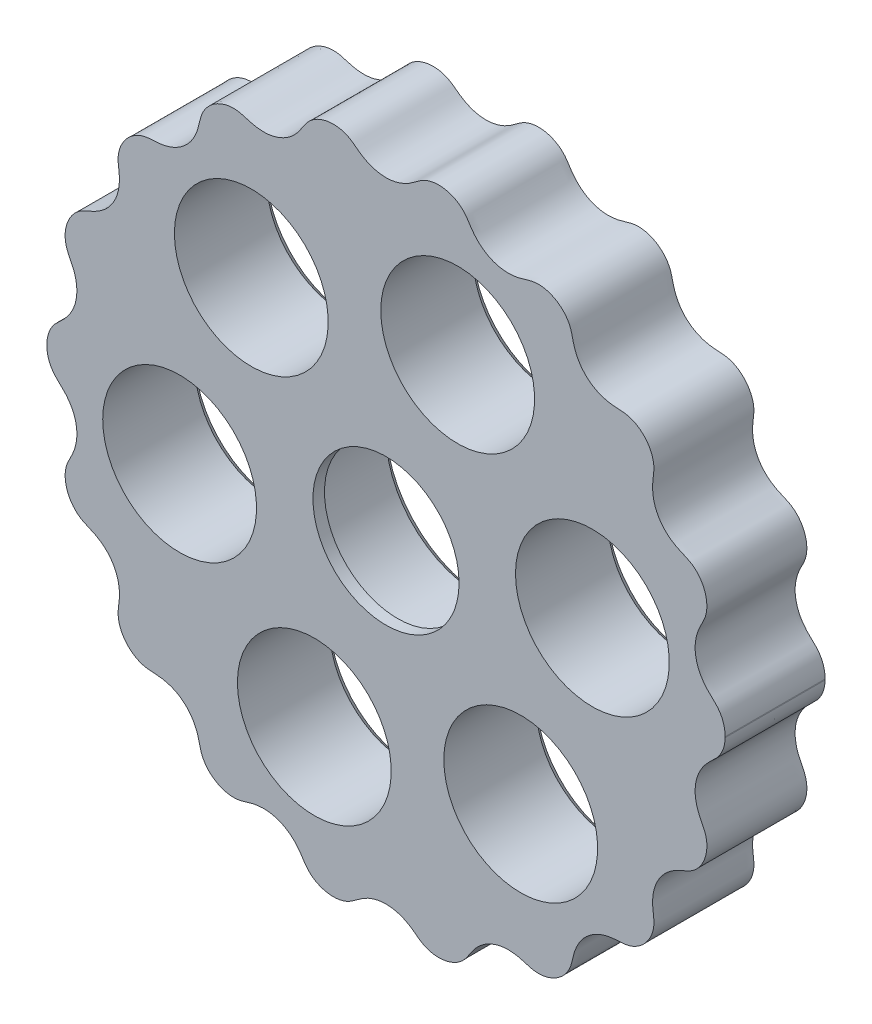
SolidWorks part; units mm, degrees
ref_plane "Front Plane" through (0, 0, 0) normal (0, 0, 1) x (1, 0, 0)
ref_plane "Top Plane" through (0, 0, 0) normal (0, 1, 0) x (1, 0, 0)
ref_plane "Right Plane" through (0, 0, 0) normal (1, 0, 0) x (0, 0, -1)
sketch "Sketch1" plane through (0, 0, 0) normal (0, 0, 1) x (1, 0, 0)
  line L0 (0, 0) -> (71.5354, 0) construction
  line L1 (0, 0) -> (26.836, 4.7319) construction
  arc A0 (44.0985, -0.1203) -> (44.1, 0) centre (39.3924, 0) ccw
  circle A1 centre (0, 0) radius 12
  circle A2 centre (26.836, 4.7319) radius 10
  circle A3 centre (17.516, -20.8747) radius 10
  circle A4 centre (-9.32, -25.6066) radius 10
  circle A5 centre (-26.836, -4.7319) radius 10
  circle A6 centre (-17.516, 20.8747) radius 10
  circle A7 centre (9.32, 25.6066) radius 10
  spline S0 degree 4 poles (36.6767, -18.9558) (36.8635, -18.7987) (37.1568, -18.579) (37.5707, -18.3184) (38.1155, -18.0434) (38.5626, -17.8474) (39.0142, -17.663) (39.4567, -17.456) (39.9012, -17.1807) (40.3307, -16.827) (40.8354, -16.2774) (41.3043, -15.523) (41.6465, -14.5868) (41.7649, -13.5582) (41.6813, -12.7422) (41.4951, -12.1162) (41.2986, -11.6694) (41.1215, -11.3218) (40.8977, -10.8888) (40.649, -10.3583) (40.4142, -9.7146) (40.1974, -8.7592) (40.1486, -7.6129) (40.3906, -6.3196) (40.9635, -5.1322) (41.587, -4.3265) (42.1201, -3.7892) (42.487, -3.4498) (42.7801, -3.1781) (43.1277, -2.8182) (43.4078, -2.4428) (43.6222, -2.0645) (43.7821, -1.6974) (43.8734, -1.446) (43.9495, -1.19) (44.0102, -0.9293) (44.0501, -0.6984) (44.0747, -0.5033) (44.0889, -0.3315) (44.0965, -0.1882) (44.1004, -0.0512) (44.1003, 0.0575) (44.0961, 0.2002) (44.0877, 0.3516) (44.0718, 0.5312) (44.0443, 0.7371) (44.0062, 0.9465) (43.9574, 1.1527) (43.9002, 1.3564) (43.8124, 1.6248) (43.6759, 1.9561) (43.4704, 2.3388) (43.1973, 2.7268) (42.9028, 3.0591) (42.5811, 3.3642) (42.2543, 3.6633) (41.857, 4.0496) (41.4472, 4.5088) (41.0516, 5.0585) (40.6188, 5.8583) (40.2694, 6.862) (40.1379, 7.9369) (40.2404, 9.0241) (40.4824, 9.9238) (40.7241, 10.5303) (40.9711, 11.0329) (41.23, 11.5305) (41.4742, 12.0369) (41.6912, 12.7506) (41.7643, 13.6759) (41.6231, 14.6695) (41.2345, 15.6741) (40.6786, 16.4957) (40.0904, 17.0544) (39.5529, 17.4028) (39.1287, 17.6105) (38.7812, 17.7582) (38.3459, 17.9401) (37.6896, 18.2421) (36.8537, 18.748) (35.9651, 19.5642) (35.2253, 20.6754) (34.8042, 21.8218) (34.6582, 22.7995) (34.6551, 23.5837) (34.7014, 24.1649) (34.7588, 24.6276) (34.819, 25.0899) (34.8465, 25.5562) (34.8182, 26.0519) (34.7221, 26.5691) (34.5055, 27.2363) (34.094, 28.0103) (33.4389, 28.7967) (32.6453, 29.3765) (31.9237, 29.701) (31.3397, 29.8541) (30.9247, 29.9174) (30.5063, 29.9454) (30.0877, 29.9633) (29.5648, 29.9977) (28.7961, 30.0962) (27.8011, 30.3642) (26.6402, 30.9641) (25.5501, 31.9548) (24.8466, 33.0536) (24.4844, 34.0219) (24.3027, 34.7493) (24.1799, 35.3002) (24.0444, 35.8492) (23.7558, 36.5419) (23.2182, 37.3055) (22.4721, 37.981) (21.5304, 38.5043) (20.5803, 38.7796) (19.7758, 38.834) (19.1432, 38.7607) (18.6866, 38.6509) (18.3273, 38.5424) (17.8796, 38.4022) (17.1879, 38.2098) (16.2295, 38.0541) (15.1511, 38.0927) (14.1001, 38.3568) (13.249, 38.7395) (12.5843, 39.159) (11.9777, 39.6706) (11.5076, 40.1878) (11.1477, 40.6723) (10.8676, 41.0971) (10.6491, 41.4405) (10.4195, 41.7769) (10.1616, 42.0928) (9.8452, 42.4081) (9.4641, 42.7096) (8.8955, 43.0565) (8.1021, 43.3731) (7.1136, 43.5515) (6.147, 43.4906) (5.3888, 43.281) (4.8443, 43.0283) (4.4861, 42.8141) (4.1483, 42.5698) (3.8181, 42.3158) (3.399, 42.0065) (2.753, 41.5865) (1.827, 41.1474) (0.5868, 40.8561) (-0.8258, 40.8878) (-2.0369, 41.2268) (-2.9229, 41.6848) (-3.5391, 42.1066) (-3.9385, 42.4083) (-4.2568, 42.6512) (-4.5868, 42.8786) (-4.9366, 43.0749) (-5.4733, 43.3086) (-6.2224, 43.5002) (-7.1565, 43.5453) (-8.2308, 43.3442) (-9.1419, 42.9461) (-9.7919, 42.4774) (-10.2304, 42.0207) (-10.5107, 41.6472) (-10.716, 41.3356) (-10.9671, 40.9426) (-11.3683, 40.3523) (-11.9933, 39.6173) (-12.9784, 38.8345) (-14.3072, 38.2427) (-15.622, 38.0386) (-16.7078, 38.119) (-17.5001, 38.2943) (-18.0183, 38.4446) (-18.4296, 38.575) (-18.8445, 38.6948) (-19.2689, 38.7773) (-19.7296, 38.8158) (-20.2217, 38.799) (-20.8742, 38.6969) (-21.6651, 38.435) (-22.5148, 37.9532) (-23.2004, 37.3139) (-23.6407, 36.7001) (-23.8979, 36.1889) (-24.0388, 35.8228) (-24.1457, 35.4456) (-24.2324, 35.0637) (-24.341, 34.5862) (-24.5432, 33.8399) (-24.9478, 32.8575) (-25.7396, 31.7268) (-26.8198, 30.8543) (-27.9055, 30.3412) (-28.8681, 30.0882) (-29.542, 29.9965) (-30.1085, 29.9625) (-30.655, 29.9382) (-31.2013, 29.8918) (-31.908, 29.7209) (-32.7236, 29.3297) (-33.437, 28.7738) (-34.0217, 28.0893) (-34.4319, 27.3875) (-34.6947, 26.7092) (-34.8184, 26.0998) (-34.8448, 25.586) (-34.8229, 25.1791) (-34.7914, 24.879) (-34.753, 24.5799) (-34.7164, 24.2805) (-34.6791, 23.9054) (-34.6547, 23.4533) (-34.6644, 22.9248) (-34.752, 22.1746) (-34.9928, 21.2469) (-35.4949, 20.1956) (-36.285, 19.2336) (-37.1129, 18.5857) (-37.8164, 18.1869) (-38.3337, 17.9455) (-38.7546, 17.7691) (-39.1754, 17.5922) (-39.5824, 17.3838) (-39.9866, 17.1147) (-40.376, 16.7794) (-40.8341, 16.2703) (-41.287, 15.5514) (-41.6373, 14.6281) (-41.7684, 13.5957) (-41.6841, 12.7484) (-41.4922, 12.1084) (-41.2953, 11.6627) (-41.1183, 11.3156) (-40.8949, 10.8831) (-40.6493, 10.3583) (-40.4186, 9.7263) (-40.2044, 8.7952) (-40.1455, 7.6523) (-40.3811, 6.3316) (-40.9655, 5.1189) (-41.6171, 4.2907) (-42.1615, 3.7501) (-42.5188, 3.4208) (-42.8029, 3.1556) (-43.1388, 2.8039) (-43.5356, 2.2681) (-43.902, 1.5016) (-44.1301, 0.4873) (-44.1153, -0.4997) (-43.9342, -1.3305) (-43.676, -1.9663) (-43.4233, -2.4149) (-43.1338, -2.8061) (-42.8211, -3.1409) (-42.4852, -3.4513) (-42.1496, -3.7619) (-41.7459, -4.1672) (-41.2216, -4.785) (-40.6667, -5.6805) (-40.2571, -6.8575) (-40.1492, -8.0179) (-40.2435, -8.9709) (-40.4198, -9.7036) (-40.5923, -10.2019) (-40.7703, -10.617) (-40.9338, -10.9558) (-41.0705, -11.2238) (-41.2084, -11.4912) (-41.3399, -11.762) (-41.4983, -12.1364) (-41.6474, -12.6276) (-41.7379, -13.2414) (-41.7216, -13.967) (-41.5738, -14.7731) (-41.2501, -15.6297) (-40.7493, -16.4152) (-40.1472, -17.0103) (-39.5948, -17.3794) (-39.1613, -17.5962) (-38.805, -17.7483) (-38.3581, -17.9346) (-37.6632, -18.2533) (-36.7684, -18.8026) (-35.9394, -19.6017) (-35.3162, -20.559) (-34.9501, -21.4361) (-34.754, -22.1735) (-34.6561, -22.9355) (-34.6539, -23.6107) (-34.7037, -24.19) (-34.7654, -24.6746) (-34.814, -25.0624) (-34.8415, -25.4527) (-34.8332, -25.844) (-34.765, -26.411) (-34.56, -27.1363) (-34.1301, -27.9767) (-33.4866, -28.7263) (-32.8171, -29.248) (-32.2156, -29.5706) (-31.7373, -29.7537) (-31.2675, -29.87) (-30.8155, -29.9284) (-30.361, -29.9515) (-29.9067, -29.9728) (-29.3398, -30.0211) (-28.5445, -30.1517) (-27.5467, -30.4714) (-26.4782, -31.095) (-25.6473, -31.8986) (-25.1024, -32.6745) (-24.7614, -33.3361) (-24.5688, -33.82) (-24.4344, -34.2453) (-24.3393, -34.6045) (-24.2708, -34.8937) (-24.2056, -35.1836) (-24.1369, -35.4728) (-24.0508, -35.7776) (-23.9368, -36.0939) (-23.7481, -36.5019) (-23.4494, -36.98) (-23.0222, -37.4813) (-22.3719, -38.029) (-21.544, -38.4954) (-20.7168, -38.7507) (-19.9455, -38.8252) (-19.36, -38.7875) (-18.9635, -38.7214) (-18.575, -38.6194) (-18.1922, -38.4994) (-17.7124, -38.3527) (-16.9871, -38.1681) (-15.9954, -38.0433) (-14.7404, -38.1435) (-13.4038, -38.602) (-12.3415, -39.3031) (-11.6253, -40.033) (-11.1642, -40.6483) (-10.8775, -41.0818) (-10.6541, -41.4324) (-10.3623, -41.8626) (-9.899, -42.3938) (-9.1869, -42.9321) (-8.2037, -43.3602) (-7.0734, -43.5529) (-6.1148, -43.4841) (-5.3713, -43.274) (-4.8379, -43.0245) (-4.4874, -42.8146) (-4.1564, -42.5758) (-3.8331, -42.3273) (-3.4233, -42.0238) (-2.7537, -41.584) (-1.7612, -41.114) (-0.4425, -40.8308) (1.0403, -40.9203) (2.2524, -41.3176) (3.0965, -41.7927) (3.6787, -42.2102) (4.0505, -42.4945) (4.3506, -42.7186) (4.7419, -42.9762) (5.3109, -43.2592) (6.0842, -43.4809) (7.0779, -43.5461) (8.1565, -43.3701) (9.0185, -43.0112) (9.656, -42.5787) (10.0808, -42.1789) (10.3429, -41.8772) (10.5757, -41.5527) (10.7913, -41.217) (11.062, -40.7981) (11.4933, -40.1917) (12.1633, -39.458) (13.1794, -38.7205) (14.4926, -38.1994) (15.7586, -38.0413) (16.7829, -38.1326) (17.5369, -38.3043) (18.0387, -38.4511) (18.4373, -38.5773) (18.8393, -38.693) (19.2503, -38.7741) (19.7068, -38.8152) (20.2045, -38.8013) (20.8784, -38.6982) (21.7056, -38.4205) (22.4637, -37.9777) (23.1147, -37.3897) (23.5463, -36.8348) (23.8129, -36.3801) (24.0082, -35.9224) (24.1409, -35.4736) (24.2423, -35.0176) (24.3472, -34.5622) (24.5038, -33.9993) (24.7774, -33.2626) (25.2526, -32.3934) (26.0445, -31.4622) (27.1225, -30.6755) (28.2369, -30.2168) (29.1936, -30.0303) (29.912, -29.9724) (30.3823, -29.9506) (30.7585, -29.9304) (31.2269, -29.8792) (31.8494, -29.734) (32.5908, -29.4093) (33.3924, -28.8267) (34.1, -28.0146) (34.5716, -27.1275) (34.818, -26.2303) (34.8559, -25.4836) (34.798, -24.9232) (34.725, -24.3656) (34.6454, -23.6229) (34.6499, -22.5928) (34.9244, -21.3341) (35.5841, -20.0498) (36.4432, -19.0874) (37.2687, -18.4847) (37.9615, -18.1146) (38.4661, -17.8887) (38.8747, -17.7199) (39.2802, -17.5429) (39.6692, -17.3307) (40.0569, -17.059) (40.4321, -16.7224) (40.8754, -16.2125) (41.3225, -15.4793) (41.6159, -14.6641) (41.7389, -13.805) (41.7166, -13.1062) (41.6324, -12.5888) (41.4921, -12.1142) (41.3092, -11.6862) (41.0959, -11.2734) (40.8838, -10.86) (40.6409, -10.3322) (40.3736, -9.5978) (40.1722, -8.6335) (40.1685, -7.4139) (40.4758, -6.1143) (41.0266, -5.0381) (41.638, -4.2711) (42.152, -3.7595) (42.4998, -3.4381) (42.7773, -3.1801) (43.1073, -2.8399) (43.4176, -2.4332) (43.6529, -2.012) (43.8242, -1.5939) (43.9238, -1.2824) (43.9889, -1.0282) (44.033, -0.8034) (44.0616, -0.6126) (44.0796, -0.4441) (44.0904, -0.304) (44.0975, -0.1709) (44.1002, -0.0646) (44.0998, 0.0735) (44.0955, 0.2206) (44.0851, 0.3964) (44.0643, 0.597) (44.0285, 0.8351) (43.9716, 1.1035) (43.8986, 1.3677) (43.8096, 1.6271) (43.6583, 1.9911) (43.4135, 2.4438) (43.0871, 2.8775) (42.6816, 3.2715) (42.2656, 3.653) (41.7268, 4.1708) (41.0686, 4.9615) (40.4759, 6.0882) (40.1559, 7.4652) (40.1801, 8.7282) (40.4033, 9.7014) (40.6813, 10.4269) (40.92, 10.9322) (41.1253, 11.3291) (41.3284, 11.7273) (41.5005, 12.1406) (41.6361, 12.607) (41.7187, 13.1243) (41.7383, 13.8359) (41.6034, 14.7228) (41.2341, 15.7008) (40.6514, 16.5314) (40.0399, 17.0906) (39.4907, 17.4365) (39.0646, 17.6413) (38.6279, 17.8207) (38.1942, 18.0075) (37.6639, 18.2672) (37.259, 18.512) (36.9707, 18.7184) (36.7863, 18.8659) knots 0 0 0 0 0 0.002836 0.004253 0.005671 0.007089 0.008507 0.009925 0.011343 0.013148 0.014954 0.018566 0.021594 0.024621 0.026888 0.028021 0.029155 0.030288 0.031421 0.033688 0.03596 0.038232 0.042776 0.046922 0.051068 0.053391 0.054552 0.055714 0.056876 0.058037 0.060361 0.061137 0.061913 0.062689 0.063466 0.064242 0.065018 0.065406 0.065795 0.066183 0.066571 0.066981 0.067391 0.067801 0.068211 0.069031 0.069851 0.070261 0.070671 0.071491 0.073132 0.074419 0.075707 0.076995 0.078282 0.07957 0.080858 0.083433 0.085425 0.087418 0.091402 0.095715 0.097871 0.100027 0.102202 0.103289 0.104376 0.106551 0.108726 0.111902 0.115078 0.118109 0.12114 0.123333 0.12443 0.125527 0.126624 0.127721 0.129914 0.133921 0.137927 0.141605 0.145284 0.147993 0.149348 0.150703 0.152057 0.153412 0.154767 0.156121 0.157815 0.159508 0.162895 0.166245 0.169595 0.170813 0.17203 0.173248 0.174466 0.175684 0.176902 0.179337 0.183463 0.187589 0.191926 0.196263 0.19845 0.199544 0.200638 0.202826 0.205013 0.208208 0.211403 0.214416 0.217428 0.219609 0.2207 0.22179 0.222881 0.223971 0.226152 0.230133 0.234114 0.236391 0.238667 0.240943 0.24322 0.245585 0.246768 0.247951 0.249134 0.250316 0.251499 0.252682 0.254316 0.255951 0.25922 0.262551 0.265882 0.267093 0.268303 0.269514 0.270725 0.271935 0.273146 0.275567 0.279672 0.283776 0.287796 0.291816 0.294143 0.295306 0.29647 0.297633 0.298797 0.29996 0.301124 0.304426 0.307727 0.310722 0.313717 0.315886 0.31697 0.318054 0.319138 0.320223 0.322391 0.326347 0.330303 0.334707 0.33911 0.341618 0.342872 0.344126 0.34538 0.346634 0.347888 0.349142 0.350743 0.352343 0.355544 0.35877 0.361996 0.363134 0.364272 0.36541 0.366548 0.367686 0.368824 0.3711 0.375531 0.379962 0.384669 0.387023 0.389377 0.391497 0.392557 0.393618 0.395738 0.397859 0.400955 0.404052 0.406156 0.40826 0.410365 0.412469 0.413345 0.414222 0.415098 0.415975 0.416851 0.417727 0.41948 0.421233 0.422985 0.426491 0.43057 0.434649 0.437302 0.438628 0.439954 0.44128 0.442607 0.443933 0.445259 0.446911 0.448564 0.451868 0.455076 0.458283 0.460547 0.461678 0.46281 0.463942 0.465074 0.467337 0.46954 0.471743 0.476148 0.480544 0.48494 0.487199 0.488328 0.489458 0.490587 0.491717 0.493975 0.497176 0.500376 0.503687 0.505343 0.506999 0.508328 0.509657 0.510985 0.512314 0.513643 0.514972 0.51763 0.521717 0.525805 0.529302 0.531051 0.5328 0.534548 0.535423 0.536297 0.537171 0.538046 0.53892 0.539794 0.541894 0.543993 0.546093 0.548193 0.551381 0.55457 0.556821 0.557947 0.559072 0.560198 0.561324 0.563575 0.567955 0.572335 0.574545 0.576756 0.578967 0.581177 0.583449 0.584584 0.58572 0.586856 0.587991 0.589127 0.590263 0.593481 0.5967 0.599994 0.601641 0.603287 0.604609 0.605931 0.607253 0.608575 0.609897 0.611219 0.613863 0.617928 0.621994 0.625448 0.627175 0.628902 0.630629 0.631492 0.632356 0.63322 0.634083 0.634947 0.63581 0.636899 0.637987 0.640164 0.64234 0.644517 0.647826 0.651135 0.652301 0.653467 0.654633 0.655799 0.656965 0.658131 0.660463 0.664492 0.668521 0.672617 0.676713 0.679129 0.680337 0.681545 0.682753 0.683961 0.686377 0.689701 0.693025 0.6963 0.699576 0.700761 0.701947 0.703132 0.704317 0.705502 0.706687 0.709058 0.71362 0.718182 0.722153 0.726125 0.728301 0.729389 0.730477 0.731565 0.732653 0.73483 0.737836 0.740842 0.744132 0.747422 0.748581 0.74974 0.7509 0.752059 0.753218 0.754378 0.756697 0.760702 0.764708 0.768825 0.772943 0.775373 0.776588 0.777804 0.779019 0.780234 0.781449 0.782664 0.784335 0.786007 0.789349 0.792743 0.79444 0.796137 0.797495 0.798852 0.80021 0.801567 0.802925 0.804282 0.806998 0.810684 0.81437 0.818367 0.822363 0.824552 0.825646 0.826741 0.827835 0.82893 0.831119 0.834143 0.837166 0.84035 0.843533 0.845713 0.847892 0.848982 0.850072 0.852251 0.856573 0.860895 0.864871 0.868848 0.871417 0.872702 0.873987 0.875272 0.876557 0.877842 0.879127 0.880763 0.8824 0.885674 0.889049 0.890737 0.892425 0.893775 0.895125 0.896475 0.897825 0.899175 0.900525 0.903225 0.906891 0.910557 0.914579 0.9186 0.920802 0.921903 0.923004 0.924105 0.925206 0.927407 0.928928 0.929689 0.930449 0.93121 0.93197 0.93235 0.93273 0.933111 0.933491 0.933889 0.934287 0.934686 0.935084 0.93588 0.936677 0.937473 0.938269 0.939066 0.939862 0.94205 0.944237 0.945331 0.946425 0.948612 0.952921 0.957229 0.96105 0.964871 0.967468 0.968766 0.970065 0.971364 0.972662 0.973961 0.97526 0.976997 0.978734 0.982209 0.985617 0.989025 0.990397 0.991769 0.99314 0.994512 0.995884 0.997256 1 1 1 1 1 construction
  spline S1 degree 4 poles (44.1, 0) (44.1, 0.0306) (44.0993, 0.0917) (44.0961, 0.2002) (44.0877, 0.3516) (44.0718, 0.5312) (44.0443, 0.7371) (44.0062, 0.9465) (43.9574, 1.1527) (43.9002, 1.3564) (43.8124, 1.6248) (43.6759, 1.9561) (43.4704, 2.3388) (43.1973, 2.7268) (42.9028, 3.0591) (42.5811, 3.3642) (42.2543, 3.6633) (41.857, 4.0496) (41.4472, 4.5088) (41.0516, 5.0585) (40.6188, 5.8583) (40.2694, 6.862) (40.1379, 7.9369) (40.2404, 9.0241) (40.4824, 9.9238) (40.7241, 10.5303) (40.9711, 11.0329) (41.23, 11.5305) (41.4742, 12.0369) (41.6912, 12.7506) (41.7643, 13.6759) (41.6231, 14.6695) (41.2345, 15.6741) (40.6786, 16.4957) (40.0904, 17.0544) (39.5529, 17.4028) (39.1287, 17.6105) (38.7812, 17.7582) (38.3459, 17.9401) (37.6896, 18.2421) (36.8537, 18.748) (35.9651, 19.5642) (35.2253, 20.6754) (34.8042, 21.8218) (34.6582, 22.7995) (34.6551, 23.5837) (34.7014, 24.1649) (34.7588, 24.6276) (34.819, 25.0899) (34.8465, 25.5562) (34.8182, 26.0519) (34.7221, 26.5691) (34.5055, 27.2363) (34.094, 28.0103) (33.4389, 28.7967) (32.6453, 29.3765) (31.9237, 29.701) (31.3397, 29.8541) (30.9247, 29.9174) (30.5063, 29.9454) (30.0877, 29.9633) (29.5648, 29.9977) (28.7961, 30.0962) (27.8011, 30.3642) (26.6402, 30.9641) (25.5501, 31.9548) (24.8466, 33.0536) (24.4844, 34.0219) (24.3027, 34.7493) (24.1799, 35.3002) (24.0444, 35.8492) (23.7558, 36.5419) (23.2182, 37.3055) (22.4721, 37.981) (21.5304, 38.5043) (20.5803, 38.7796) (19.7758, 38.834) (19.1432, 38.7607) (18.6866, 38.6509) (18.3273, 38.5424) (17.8796, 38.4022) (17.1879, 38.2098) (16.2295, 38.0541) (15.1511, 38.0927) (14.1001, 38.3568) (13.249, 38.7395) (12.5843, 39.159) (11.9777, 39.6706) (11.5076, 40.1878) (11.1477, 40.6723) (10.8676, 41.0971) (10.6491, 41.4405) (10.4195, 41.7769) (10.1616, 42.0928) (9.8452, 42.4081) (9.4641, 42.7096) (8.8955, 43.0565) (8.1021, 43.3731) (7.1136, 43.5515) (6.147, 43.4906) (5.3888, 43.281) (4.8443, 43.0283) (4.4861, 42.8141) (4.1483, 42.5698) (3.8181, 42.3158) (3.399, 42.0065) (2.753, 41.5865) (1.827, 41.1474) (0.5868, 40.8561) (-0.8258, 40.8878) (-2.0369, 41.2268) (-2.9229, 41.6848) (-3.5391, 42.1066) (-3.9385, 42.4083) (-4.2568, 42.6512) (-4.5868, 42.8786) (-4.9366, 43.0749) (-5.4733, 43.3086) (-6.2224, 43.5002) (-7.1565, 43.5453) (-8.2308, 43.3442) (-9.1419, 42.9461) (-9.7919, 42.4774) (-10.2304, 42.0207) (-10.5107, 41.6472) (-10.716, 41.3356) (-10.9671, 40.9426) (-11.3683, 40.3523) (-11.9933, 39.6173) (-12.9784, 38.8345) (-14.3072, 38.2427) (-15.622, 38.0386) (-16.7078, 38.119) (-17.5001, 38.2943) (-18.0183, 38.4446) (-18.4296, 38.575) (-18.8445, 38.6948) (-19.2689, 38.7773) (-19.7296, 38.8158) (-20.2217, 38.799) (-20.8742, 38.6969) (-21.6651, 38.435) (-22.5148, 37.9532) (-23.2004, 37.3139) (-23.6407, 36.7001) (-23.8979, 36.1889) (-24.0388, 35.8228) (-24.1457, 35.4456) (-24.2324, 35.0637) (-24.341, 34.5862) (-24.5432, 33.8399) (-24.9478, 32.8575) (-25.7396, 31.7268) (-26.8198, 30.8543) (-27.9055, 30.3412) (-28.8681, 30.0882) (-29.542, 29.9965) (-30.1085, 29.9625) (-30.655, 29.9382) (-31.2013, 29.8918) (-31.908, 29.7209) (-32.7236, 29.3297) (-33.437, 28.7738) (-34.0217, 28.0893) (-34.4319, 27.3875) (-34.6947, 26.7092) (-34.8184, 26.0998) (-34.8448, 25.586) (-34.8229, 25.1791) (-34.7914, 24.879) (-34.753, 24.5799) (-34.7164, 24.2805) (-34.6791, 23.9054) (-34.6547, 23.4533) (-34.6644, 22.9248) (-34.752, 22.1746) (-34.9928, 21.2469) (-35.4949, 20.1956) (-36.285, 19.2336) (-37.1129, 18.5857) (-37.8164, 18.1869) (-38.3337, 17.9455) (-38.7546, 17.7691) (-39.1754, 17.5922) (-39.5824, 17.3838) (-39.9866, 17.1147) (-40.376, 16.7794) (-40.8341, 16.2703) (-41.287, 15.5514) (-41.6373, 14.6281) (-41.7684, 13.5957) (-41.6841, 12.7484) (-41.4922, 12.1084) (-41.2953, 11.6627) (-41.1183, 11.3156) (-40.8949, 10.8831) (-40.6493, 10.3583) (-40.4186, 9.7263) (-40.2044, 8.7952) (-40.1455, 7.6523) (-40.3811, 6.3316) (-40.9655, 5.1189) (-41.6171, 4.2907) (-42.1615, 3.7501) (-42.5188, 3.4208) (-42.8029, 3.1556) (-43.1388, 2.8039) (-43.5356, 2.2681) (-43.902, 1.5016) (-44.1301, 0.4873) (-44.1153, -0.4997) (-43.9342, -1.3305) (-43.676, -1.9663) (-43.4233, -2.4149) (-43.1338, -2.8061) (-42.8211, -3.1409) (-42.4852, -3.4513) (-42.1496, -3.7619) (-41.7459, -4.1672) (-41.2216, -4.785) (-40.6667, -5.6805) (-40.2571, -6.8575) (-40.1492, -8.0179) (-40.2435, -8.9709) (-40.4198, -9.7036) (-40.5923, -10.2019) (-40.7703, -10.617) (-40.9338, -10.9558) (-41.0705, -11.2238) (-41.2084, -11.4912) (-41.3399, -11.762) (-41.4983, -12.1364) (-41.6474, -12.6276) (-41.7379, -13.2414) (-41.7216, -13.967) (-41.5738, -14.7731) (-41.2501, -15.6297) (-40.7493, -16.4152) (-40.1472, -17.0103) (-39.5948, -17.3794) (-39.1613, -17.5962) (-38.805, -17.7483) (-38.3581, -17.9346) (-37.6632, -18.2533) (-36.7684, -18.8026) (-35.9394, -19.6017) (-35.3162, -20.559) (-34.9501, -21.4361) (-34.754, -22.1735) (-34.6561, -22.9355) (-34.6539, -23.6107) (-34.7037, -24.19) (-34.7654, -24.6746) (-34.814, -25.0624) (-34.8415, -25.4527) (-34.8332, -25.844) (-34.765, -26.411) (-34.56, -27.1363) (-34.1301, -27.9767) (-33.4866, -28.7263) (-32.8171, -29.248) (-32.2156, -29.5706) (-31.7373, -29.7537) (-31.2675, -29.87) (-30.8155, -29.9284) (-30.361, -29.9515) (-29.9067, -29.9728) (-29.3398, -30.0211) (-28.5445, -30.1517) (-27.5467, -30.4714) (-26.4782, -31.095) (-25.6473, -31.8986) (-25.1024, -32.6745) (-24.7614, -33.3361) (-24.5688, -33.82) (-24.4344, -34.2453) (-24.3393, -34.6045) (-24.2708, -34.8937) (-24.2056, -35.1836) (-24.1369, -35.4728) (-24.0508, -35.7776) (-23.9368, -36.0939) (-23.7481, -36.5019) (-23.4494, -36.98) (-23.0222, -37.4813) (-22.3719, -38.029) (-21.544, -38.4954) (-20.7168, -38.7507) (-19.9455, -38.8252) (-19.36, -38.7875) (-18.9635, -38.7214) (-18.575, -38.6194) (-18.1922, -38.4994) (-17.7124, -38.3527) (-16.9871, -38.1681) (-15.9954, -38.0433) (-14.7404, -38.1435) (-13.4038, -38.602) (-12.3415, -39.3031) (-11.6253, -40.033) (-11.1642, -40.6483) (-10.8775, -41.0818) (-10.6541, -41.4324) (-10.3623, -41.8626) (-9.899, -42.3938) (-9.1869, -42.9321) (-8.2037, -43.3602) (-7.0734, -43.5529) (-6.1148, -43.4841) (-5.3713, -43.274) (-4.8379, -43.0245) (-4.4874, -42.8146) (-4.1564, -42.5758) (-3.8331, -42.3273) (-3.4233, -42.0238) (-2.7537, -41.584) (-1.7612, -41.114) (-0.4425, -40.8308) (1.0403, -40.9203) (2.2524, -41.3176) (3.0965, -41.7927) (3.6787, -42.2102) (4.0505, -42.4945) (4.3506, -42.7186) (4.7419, -42.9762) (5.3109, -43.2592) (6.0842, -43.4809) (7.0779, -43.5461) (8.1565, -43.3701) (9.0185, -43.0112) (9.656, -42.5787) (10.0808, -42.1789) (10.3429, -41.8772) (10.5757, -41.5527) (10.7913, -41.217) (11.062, -40.7981) (11.4933, -40.1917) (12.1633, -39.458) (13.1794, -38.7205) (14.4926, -38.1994) (15.7586, -38.0413) (16.7829, -38.1326) (17.5369, -38.3043) (18.0387, -38.4511) (18.4373, -38.5773) (18.8393, -38.693) (19.2503, -38.7741) (19.7068, -38.8152) (20.2045, -38.8013) (20.8784, -38.6982) (21.7056, -38.4205) (22.4637, -37.9777) (23.1147, -37.3897) (23.5463, -36.8348) (23.8129, -36.3801) (24.0082, -35.9224) (24.1409, -35.4736) (24.2423, -35.0176) (24.3472, -34.5622) (24.5038, -33.9993) (24.7774, -33.2626) (25.2526, -32.3934) (26.0445, -31.4622) (27.1225, -30.6755) (28.2369, -30.2168) (29.1936, -30.0303) (29.912, -29.9724) (30.3823, -29.9506) (30.7585, -29.9304) (31.2269, -29.8792) (31.8494, -29.734) (32.5908, -29.4093) (33.3924, -28.8267) (34.1, -28.0146) (34.5716, -27.1275) (34.818, -26.2303) (34.8559, -25.4836) (34.798, -24.9232) (34.725, -24.3656) (34.6454, -23.6229) (34.6499, -22.5928) (34.9244, -21.3341) (35.5841, -20.0498) (36.4432, -19.0874) (37.2687, -18.4847) (37.9615, -18.1146) (38.4661, -17.8887) (38.8747, -17.7199) (39.2802, -17.5429) (39.6692, -17.3307) (40.0569, -17.059) (40.4321, -16.7224) (40.8754, -16.2125) (41.3225, -15.4793) (41.6159, -14.6641) (41.7389, -13.805) (41.7166, -13.1062) (41.6324, -12.5888) (41.4921, -12.1142) (41.3092, -11.6862) (41.0959, -11.2734) (40.8838, -10.86) (40.6409, -10.3322) (40.3736, -9.5978) (40.1722, -8.6335) (40.1685, -7.4139) (40.4758, -6.1143) (41.0266, -5.0381) (41.638, -4.2711) (42.152, -3.7595) (42.4998, -3.4381) (42.7773, -3.1801) (43.1073, -2.8399) (43.4176, -2.4332) (43.6529, -2.012) (43.8242, -1.5939) (43.9238, -1.2824) (43.9889, -1.0282) (44.033, -0.8034) (44.0616, -0.6126) (44.0796, -0.4441) (44.0904, -0.304) (44.0957, -0.2053) (44.0977, -0.1486) (44.0985, -0.1203) knots 0.066571 0.066571 0.066571 0.066571 0.066571 0.066981 0.067391 0.067801 0.068211 0.069031 0.069851 0.070261 0.070671 0.071491 0.073132 0.074419 0.075707 0.076995 0.078282 0.07957 0.080858 0.083433 0.085425 0.087418 0.091402 0.095715 0.097871 0.100027 0.102202 0.103289 0.104376 0.106551 0.108726 0.111902 0.115078 0.118109 0.12114 0.123333 0.12443 0.125527 0.126624 0.127721 0.129914 0.133921 0.137927 0.141605 0.145284 0.147993 0.149348 0.150703 0.152057 0.153412 0.154767 0.156121 0.157815 0.159508 0.162895 0.166245 0.169595 0.170813 0.17203 0.173248 0.174466 0.175684 0.176902 0.179337 0.183463 0.187589 0.191926 0.196263 0.19845 0.199544 0.200638 0.202826 0.205013 0.208208 0.211403 0.214416 0.217428 0.219609 0.2207 0.22179 0.222881 0.223971 0.226152 0.230133 0.234114 0.236391 0.238667 0.240943 0.24322 0.245585 0.246768 0.247951 0.249134 0.250316 0.251499 0.252682 0.254316 0.255951 0.25922 0.262551 0.265882 0.267093 0.268303 0.269514 0.270725 0.271935 0.273146 0.275567 0.279672 0.283776 0.287796 0.291816 0.294143 0.295306 0.29647 0.297633 0.298797 0.29996 0.301124 0.304426 0.307727 0.310722 0.313717 0.315886 0.31697 0.318054 0.319138 0.320223 0.322391 0.326347 0.330303 0.334707 0.33911 0.341618 0.342872 0.344126 0.34538 0.346634 0.347888 0.349142 0.350743 0.352343 0.355544 0.35877 0.361996 0.363134 0.364272 0.36541 0.366548 0.367686 0.368824 0.3711 0.375531 0.379962 0.384669 0.387023 0.389377 0.391497 0.392557 0.393618 0.395738 0.397859 0.400955 0.404052 0.406156 0.40826 0.410365 0.412469 0.413345 0.414222 0.415098 0.415975 0.416851 0.417727 0.41948 0.421233 0.422985 0.426491 0.43057 0.434649 0.437302 0.438628 0.439954 0.44128 0.442607 0.443933 0.445259 0.446911 0.448564 0.451868 0.455076 0.458283 0.460547 0.461678 0.46281 0.463942 0.465074 0.467337 0.46954 0.471743 0.476148 0.480544 0.48494 0.487199 0.488328 0.489458 0.490587 0.491717 0.493975 0.497176 0.500376 0.503687 0.505343 0.506999 0.508328 0.509657 0.510985 0.512314 0.513643 0.514972 0.51763 0.521717 0.525805 0.529302 0.531051 0.5328 0.534548 0.535423 0.536297 0.537171 0.538046 0.53892 0.539794 0.541894 0.543993 0.546093 0.548193 0.551381 0.55457 0.556821 0.557947 0.559072 0.560198 0.561324 0.563575 0.567955 0.572335 0.574545 0.576756 0.578967 0.581177 0.583449 0.584584 0.58572 0.586856 0.587991 0.589127 0.590263 0.593481 0.5967 0.599994 0.601641 0.603287 0.604609 0.605931 0.607253 0.608575 0.609897 0.611219 0.613863 0.617928 0.621994 0.625448 0.627175 0.628902 0.630629 0.631492 0.632356 0.63322 0.634083 0.634947 0.63581 0.636899 0.637987 0.640164 0.64234 0.644517 0.647826 0.651135 0.652301 0.653467 0.654633 0.655799 0.656965 0.658131 0.660463 0.664492 0.668521 0.672617 0.676713 0.679129 0.680337 0.681545 0.682753 0.683961 0.686377 0.689701 0.693025 0.6963 0.699576 0.700761 0.701947 0.703132 0.704317 0.705502 0.706687 0.709058 0.71362 0.718182 0.722153 0.726125 0.728301 0.729389 0.730477 0.731565 0.732653 0.73483 0.737836 0.740842 0.744132 0.747422 0.748581 0.74974 0.7509 0.752059 0.753218 0.754378 0.756697 0.760702 0.764708 0.768825 0.772943 0.775373 0.776588 0.777804 0.779019 0.780234 0.781449 0.782664 0.784335 0.786007 0.789349 0.792743 0.79444 0.796137 0.797495 0.798852 0.80021 0.801567 0.802925 0.804282 0.806998 0.810684 0.81437 0.818367 0.822363 0.824552 0.825646 0.826741 0.827835 0.82893 0.831119 0.834143 0.837166 0.84035 0.843533 0.845713 0.847892 0.848982 0.850072 0.852251 0.856573 0.860895 0.864871 0.868848 0.871417 0.872702 0.873987 0.875272 0.876557 0.877842 0.879127 0.880763 0.8824 0.885674 0.889049 0.890737 0.892425 0.893775 0.895125 0.896475 0.897825 0.899175 0.900525 0.903225 0.906891 0.910557 0.914579 0.9186 0.920802 0.921903 0.923004 0.924105 0.925206 0.927407 0.928928 0.929689 0.930449 0.93121 0.93197 0.93235 0.93273 0.933111 0.933491 0.933491 0.933491 0.933491 0.933491
  point P22 (0, 0)
  dimension "D1" = 24
  dimension "D2" = 20
  dimension "D3" = 27.25
  dimension "D5" = 10
  dimension "D4" = 6
extrude "Boss-Extrude1" add sketch "Sketch1" along normal mid plane 13
sketch "Sketch2" plane through (0, 0, 6.5) normal (0, 0, 1) x (1, 0, 0)
  circle A0 centre (0, 0) radius 12 construction
  circle A1 centre (0, 0) radius 12
  circle A2 centre (0, 0) radius 9.5
  dimension "D1" = 2.5
extrude "Boss-Extrude2" add sketch "Sketch2" against normal blind 1.5
chamfer "Chamfer1" distance 1 angle 45 7 edges at (-7.516, 20.8747, -6.5) (19.32, 25.6066, -6.5) (36.836, 4.7319, -6.5) (12, 0, -6.5) (27.516, -20.8747, -6.5) (0.68, -25.6066, -6.5) (-16.836, -4.7319, -6.5)
sketch "Sketch3" plane through (0, 0, -6.5) normal (0, 0, -1) x (-1, 0, 0)
  circle A0 centre (32.8036, 11.8554) radius 2
  point P2 (32.8036, 11.8554)
  point P3 (0, 0)
  dimension "D1" = 4
extrude "Cut-Extrude1" cut sketch "Sketch3" against normal blind 1
